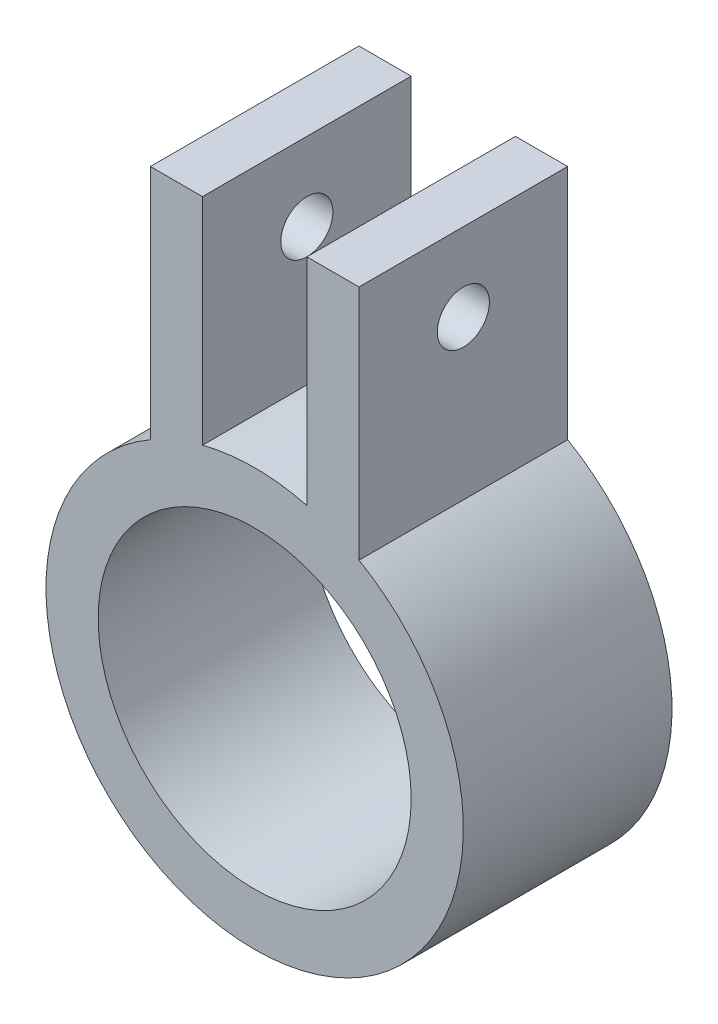
SolidWorks part; units mm, degrees
ref_plane "前视基准面" through (0, 0, 0) normal (0, 0, 1) x (1, 0, 0)
ref_plane "上视基准面" through (0, 0, 0) normal (0, 1, 0) x (1, 0, 0)
ref_plane "右视基准面" through (0, 0, 0) normal (1, 0, 0) x (0, 0, -1)
sketch "草图1" plane through (0, 0, 0) normal (0, 0, 1) x (1, 0, 0)
  line L0 (0, 3) -> (1, 3)
  line L1 (1, 3) -> (1, 8)
  line L2 (1, 8) -> (-1, 8)
  line L3 (-1, 8) -> (-1, 3)
  line L4 (-1, 3) -> (0, 3)
  line L5 (-1, 8) -> (-2, 8)
  line L6 (-2, 8) -> (-2, 2.2361)
  line L7 (0, 3) -> (0, 8)
  line L8 (1, 8) -> (2, 8)
  line L9 (2, 8) -> (2, 2.2361)
  circle A0 centre (0, 0) radius 3
  circle A1 centre (0, 0) radius 4
extrude "凸台-拉伸4" add sketch "草图1" along normal blind 4 contours L6 A1 L9 A0 | L9 A1 L1 L0 A0 | L3 A1 L6 A0 L4 | L7 A1 L3 L4 | L1 A1 L7 L0 | A1 L9 L8 L1 | A1 L3 L5 L6
sketch "草图5" plane through (-2, 0, 0) normal (-1, 0, 0) x (0, 0, 1)
  line L0 (0, 8) -> (0, 6.5)
  line L2 (0, 8) -> (0, 3.4641) construction
  line L3 (4, 8) -> (4, 3.4641) construction
  line L4 (4, 4) -> (4, 8)
  line L5 (0, 6.5) -> (2, 6.5)
  circle A0 centre (2, 6.5) radius 0.5
extrude "切除-拉伸2" cut sketch "草图5" against normal blind 4
